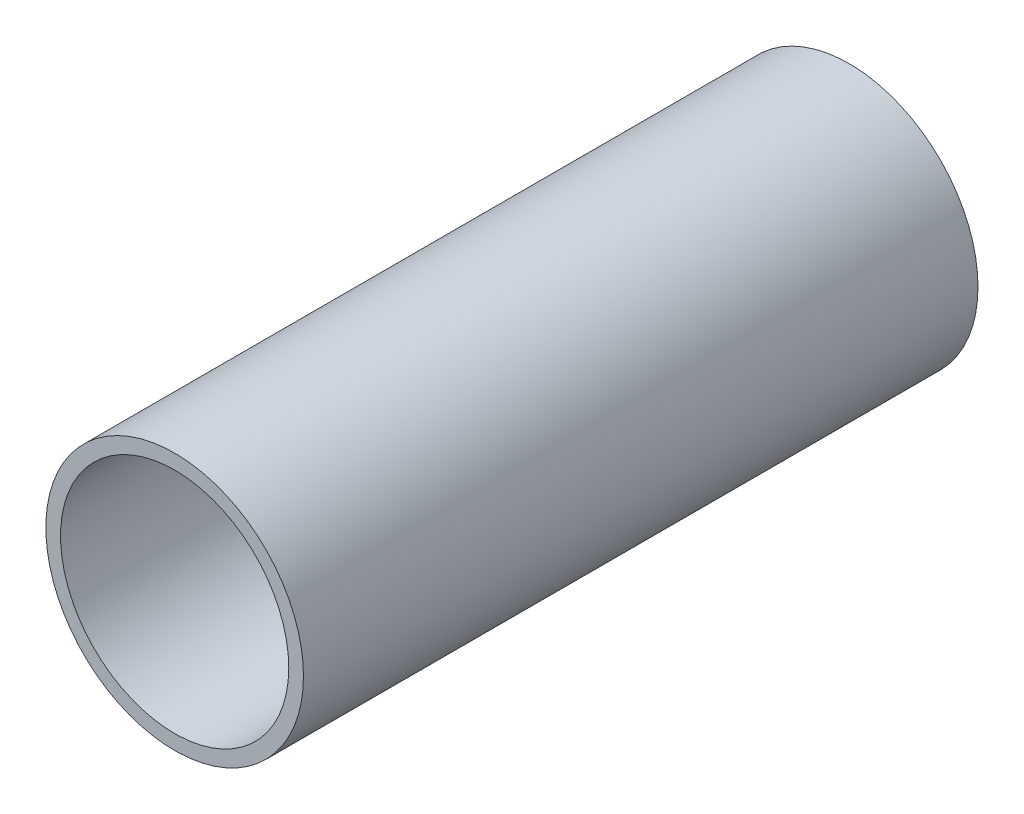
SolidWorks part; units mm, degrees
ref_plane "Plan de face" through (0, 0, 0) normal (0, 0, 1) x (1, 0, 0)
ref_plane "Plan de dessus" through (0, 0, 0) normal (0, 1, 0) x (1, 0, 0)
ref_plane "Plan de droite" through (0, 0, 0) normal (1, 0, 0) x (0, 0, -1)
sketch "Esquisse1" plane through (0, 0, 0) normal (0, 0, 1) x (1, 0, 0)
  circle A0 centre (0, 0) radius 50.5
  circle A1 centre (0, 0) radius 57
  dimension "D1" = 114
  dimension "D2" = 101
extrude "Boss.-Extru.1" add sketch "Esquisse1" along normal blind 298.5
